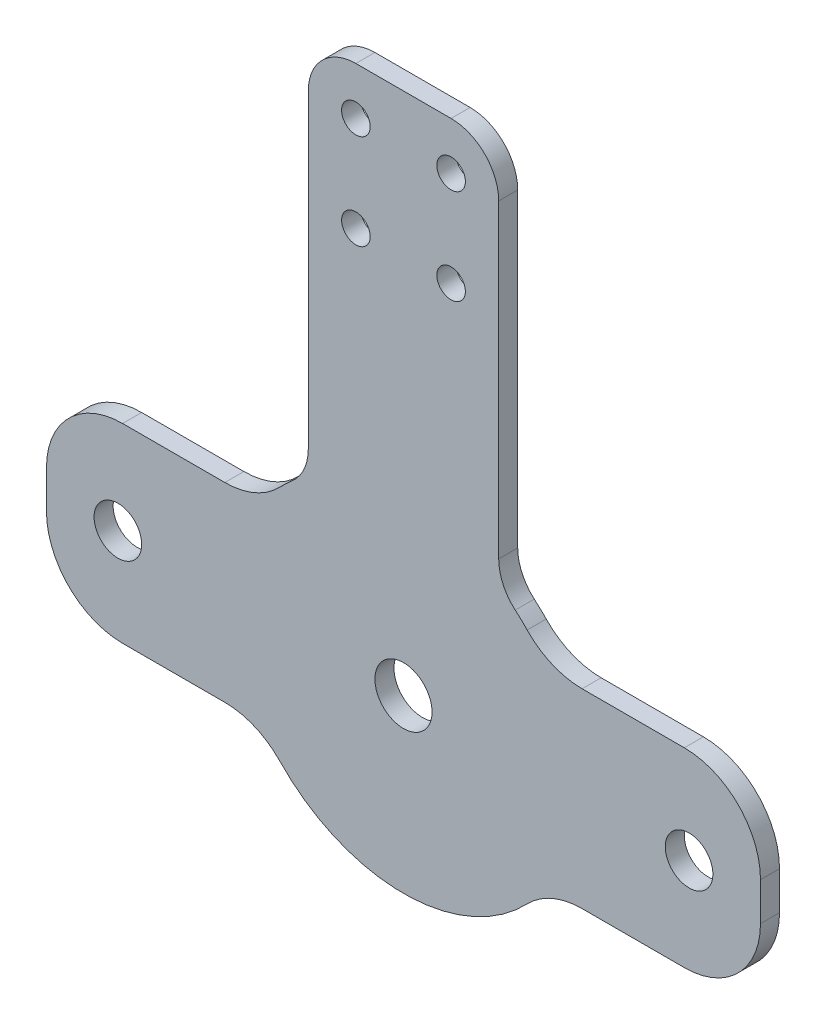
SolidWorks part; units mm, degrees
ref_plane "前视基准面" through (0, 0, 0) normal (0, 0, 1) x (1, 0, 0)
ref_plane "上视基准面" through (0, 0, 0) normal (0, 1, 0) x (1, 0, 0)
ref_plane "右视基准面" through (0, 0, 0) normal (1, 0, 0) x (0, 0, -1)
sketch "草图1" plane through (0, 0, 0) normal (0, 0, 1) x (1, 0, 0)
  circle A0 centre (0, 0) radius 18
  circle A4 centre (0, 0) radius 3
  point P7 (0, 0)
  point P13 (0, -3)
extrude "凸台-拉伸1" add sketch "草图1" along normal blind 2
sketch "草图2" plane through (0, 0, 2) normal (0, 0, 1) x (1, 0, 0)
  line L0 (-14.9666, 10) -> (-14.9666, -10)
  line L2 (-37.5, 10) -> (-37.5, -10)
  line L4 (37.5, 10) -> (37.5, -10)
  line L5 (-37.5, 10) -> (37.5, -10) construction
  line L6 (-37.5, -10) -> (37.5, 10) construction
  line L7 (37.5, 10) -> (14.9666, 10)
  line L8 (14.9666, 10) -> (14.9666, -10)
  line L9 (-37.5, 10) -> (-14.9666, 10)
  line L10 (-37.5, -10) -> (-14.9666, -10)
  line L11 (14.9666, -10) -> (37.5, -10)
  circle A0 centre (-30, 0) radius 2.5
  circle A1 centre (30, 0) radius 2.5
  point P0 (0, 0)
extrude "凸台-拉伸2" add sketch "草图2" against normal blind 2
sketch "草图3" plane through (0, 0, 2) normal (0, 0, 1) x (1, 0, 0)
  line L0 (-10, 10) -> (-10, 55)
  line L1 (-10, 55) -> (10, 55)
  line L2 (10, 10) -> (10, 55)
  line L3 (-10, 10) -> (10, 10)
  circle A0 centre (-5, 50) radius 1.5
  circle A1 centre (-5, 40) radius 1.5
  circle A2 centre (5, 40) radius 1.5
  circle A3 centre (5, 50) radius 1.5
  point P0 (4.5895, 20.3232)
  point P5 (4.5895, 5.3232)
  point P7 (4.5895, 20.3232)
extrude "凸台-拉伸3" add sketch "草图3" against normal blind 2
fillet "圆角1" radius 5 4 edges at (-10, 14.9666, 1) (10, 14.9666, 1) (10, 55, 1) (-10, 55, 1)
fillet "圆角2" radius 8 8 edges at (-14.9666, -10, 1) (14.9666, -10, 1) (37.5, -10, 1) (37.5, 10, 1) (14.9666, 10, 1) (-37.5, -10, 1) (-37.5, 10, 1) (-14.9666, 10, 1)
